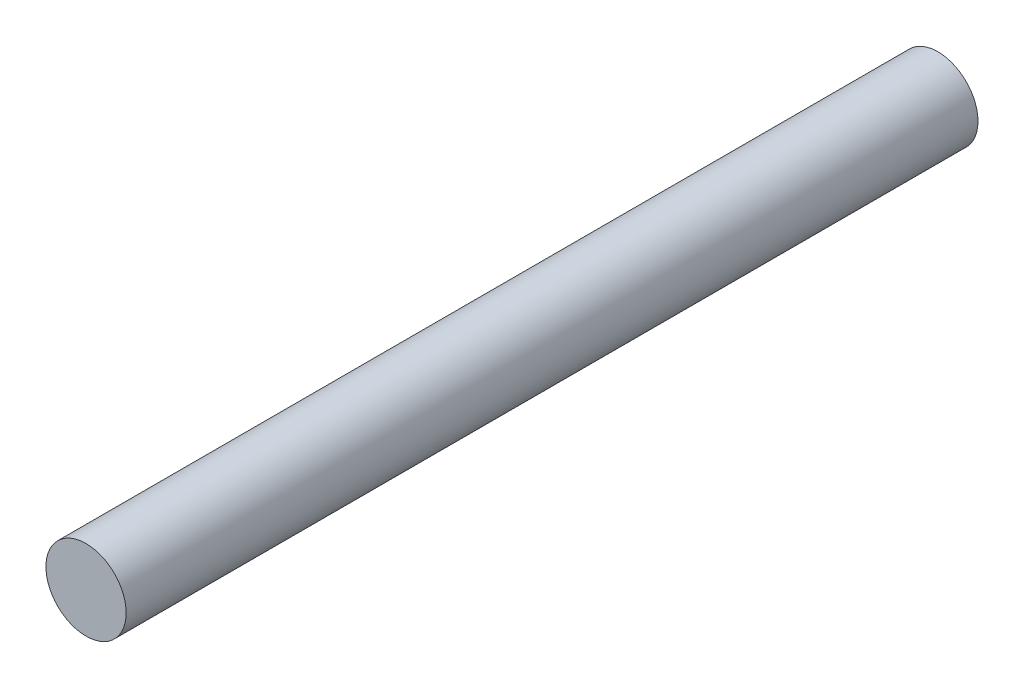
SolidWorks part; units mm, degrees
ref_plane "Front Plane" through (0, 0, 0) normal (0, 0, 1) x (1, 0, 0)
ref_plane "Top Plane" through (0, 0, 0) normal (0, 1, 0) x (1, 0, 0)
ref_plane "Right Plane" through (0, 0, 0) normal (1, 0, 0) x (0, 0, -1)
sketch "Sketch1" plane through (0, 0, 0) normal (0, 0, 1) x (1, 0, 0)
  circle A0 centre (0, 0) radius 4.05
  dimension "D1" = 8.1
extrude "Boss-Extrude1" add sketch "Sketch1" along normal blind 86
